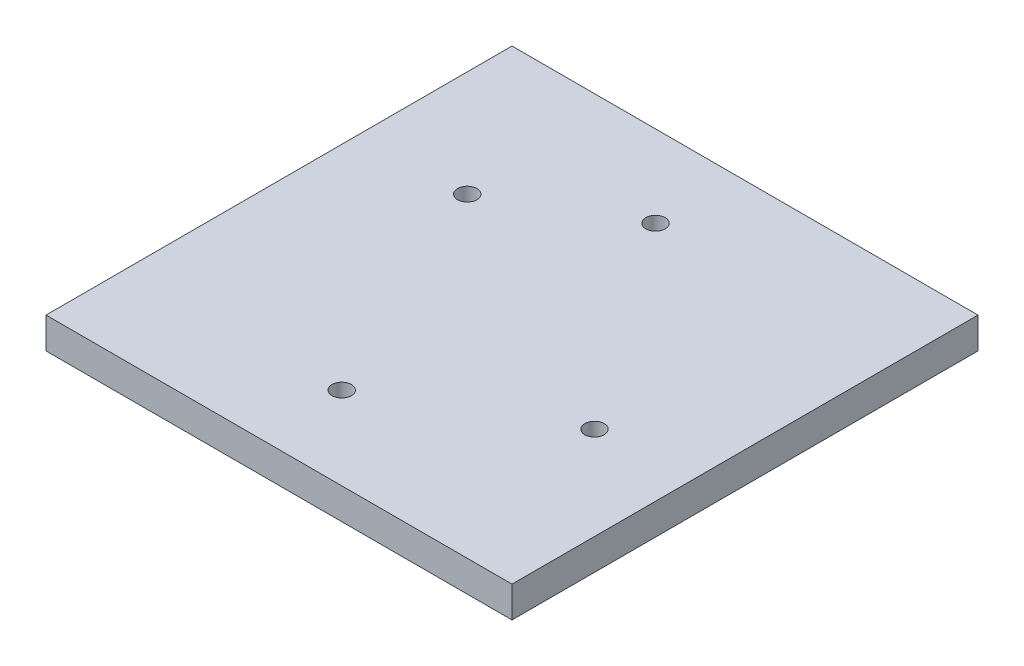
SolidWorks part; units mm, degrees
ref_plane "Front Plane" through (0, 0, 0) normal (0, 0, 1) x (1, 0, 0)
ref_plane "Top Plane" through (0, 0, 0) normal (0, 1, 0) x (1, 0, 0)
ref_plane "Right Plane" through (0, 0, 0) normal (1, 0, 0) x (0, 0, -1)
sketch "Sketch1" plane through (0, 0, 0) normal (0, 1, 0) x (1, 0, 0)
  line L1 (-76.2, -76.2) -> (76.2, -76.2)
  line L2 (-76.2, -76.2) -> (-76.2, 76.2)
  line L3 (-76.2, 76.2) -> (76.2, 76.2)
  line L4 (76.2, -76.2) -> (76.2, 76.2)
  line L5 (-76.2, -76.2) -> (76.2, 76.2) construction
  line L6 (-76.2, 76.2) -> (76.2, -76.2) construction
  point P0 (0, 0)
  dimension "D1" = 152.4
  dimension "D2" = 152.4
extrude "Boss-Extrude1" add sketch "Sketch1" along normal blind 10.16
sketch "Sketch3" plane through (0, 0, 0) normal (0, -1, 0) x (1, 0, 0)
  circle A0 centre (0, 0) radius 38.1
  dimension "D1" = 76.2
extrude "Boss-Extrude3" add sketch "Sketch3" along normal blind 12.7
sketch "Sketch4" plane through (0, -12.7, 0) normal (0, -1, 0) x (1, 0, 0)
  circle A0 centre (0, 0) radius 4
  dimension "D1" = 8
extrude "Boss-Extrude4" add sketch "Sketch4" along normal blind 18
sketch "Sketch6" plane through (0, 10.16, 0) normal (0, 1, 0) x (1, 0, 0)
  circle A0 centre (-2.5319, 49.4652) radius 3.175 construction
  circle A1 centre (-41.5722, 26.9253) radius 3.175 construction
  circle A2 centre (45.8097, -18.8333) radius 3.175 construction
  circle A3 centre (-6.5948, -49.089) radius 3.175 construction
  circle A4 centre (-2.5319, 49.4652) radius 3.175
  circle A5 centre (-41.5722, 26.9253) radius 3.175
  circle A6 centre (45.8097, -18.8333) radius 3.175
  circle A7 centre (-6.5948, -49.089) radius 3.175
sketch "Sketch7" plane through (0, 10.16, 0) normal (0, 1, 0) x (1, 0, 0)
  circle A0 centre (-41.5722, 26.9253) radius 3.175
  circle A1 centre (-2.5319, 49.4652) radius 3.175
  circle A2 centre (-6.5948, -49.089) radius 3.175
  circle A3 centre (45.8097, -18.8333) radius 3.175
extrude "Cut-Extrude2" cut sketch "Sketch7" against normal up to surface (10.16 mm away) up to face at (0, 0, -38.1)
